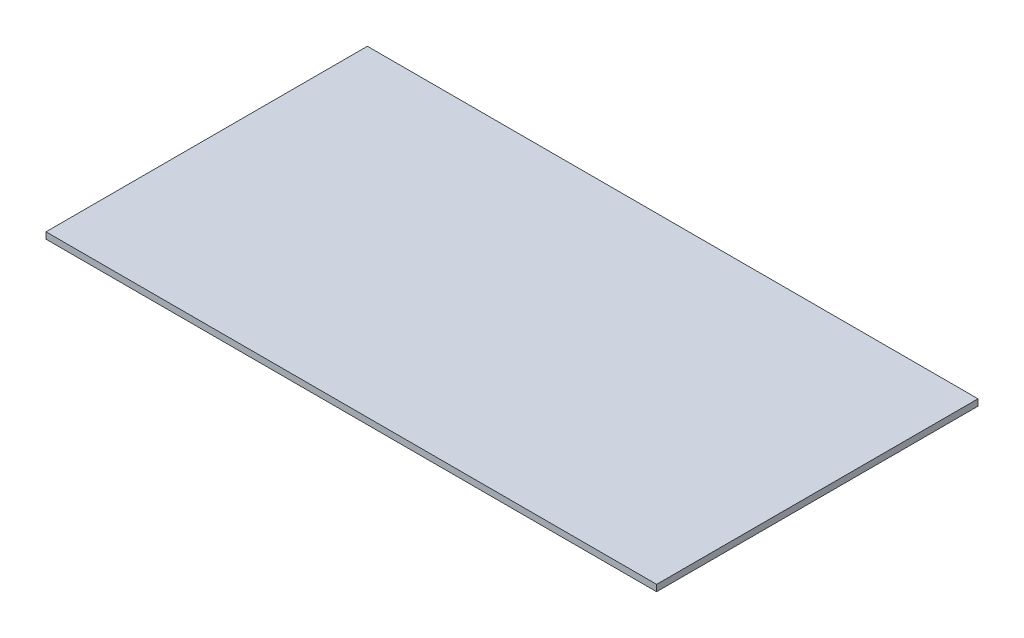
SolidWorks part; units mm, degrees
ref_plane "Front Plane" through (0, 0, 0) normal (0, 0, 1) x (1, 0, 0)
ref_plane "Top Plane" through (0, 0, 0) normal (0, 1, 0) x (1, 0, 0)
ref_plane "Right Plane" through (0, 0, 0) normal (1, 0, 0) x (0, 0, -1)
sketch "Sketch1" plane through (0, 0, 0) normal (0, 1, 0) x (1, 0, 0)
  line L1 (0, 0) -> (190, 0)
  line L2 (0, 0) -> (0, 100)
  line L3 (0, 100) -> (190, 100)
  line L4 (190, 0) -> (190, 100)
  dimension "D1" = 190
  dimension "D2" = 100
extrude "Boss-Extrude1" add sketch "Sketch1" along normal blind 2
sketch "Sketch2" plane through (0, 2, 0) normal (0, 1, 0) x (1, 0, 0)
  line L0 (190, 90) -> (0, 90) construction
  line L1 (190, 0) -> (190, 100) construction
  line L2 (0, 100) -> (0, 0) construction
  line L3 (190, 100) -> (0, 100) construction
  circle A0 centre (165, 90) radius 1.5
  circle A1 centre (25, 90) radius 1.5
  dimension "D2" = 3
  dimension "D3" = 3
  dimension "D5" = 25
  dimension "D1" = 10
  dimension "D4" = 140
